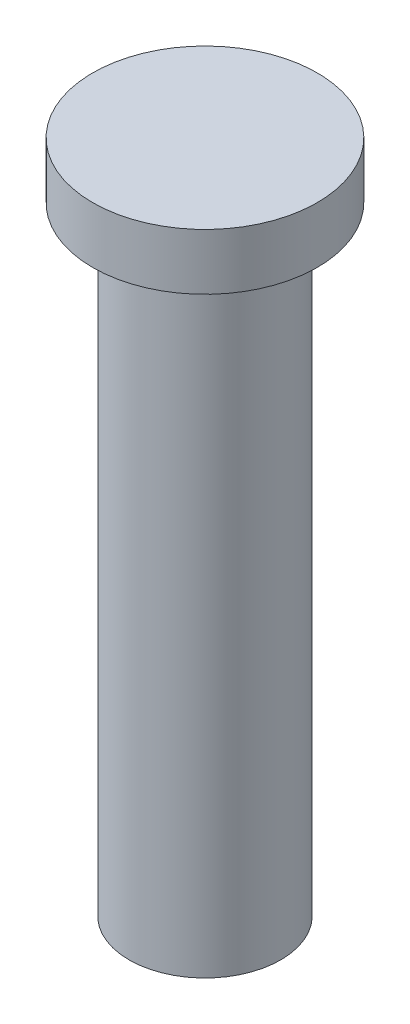
SolidWorks part; units mm, degrees
ref_plane "Front Plane" through (0, 0, 0) normal (0, 0, 1) x (1, 0, 0)
ref_plane "Top Plane" through (0, 0, 0) normal (0, 1, 0) x (1, 0, 0)
ref_plane "Right Plane" through (0, 0, 0) normal (1, 0, 0) x (0, 0, -1)
sketch "Sketch1" plane through (0, 0, 0) normal (0, 1, 0) x (1, 0, 0)
  circle A0 centre (0, 0) radius 1.35
extrude "Boss-Extrude1" add sketch "Sketch1" along normal blind 11
sketch "Sketch2" plane through (0, 11, 0) normal (0, 1, 0) x (1, 0, 0)
  circle A0 centre (0, 0) radius 2
extrude "Boss-Extrude2" add sketch "Sketch2" along normal blind 1
